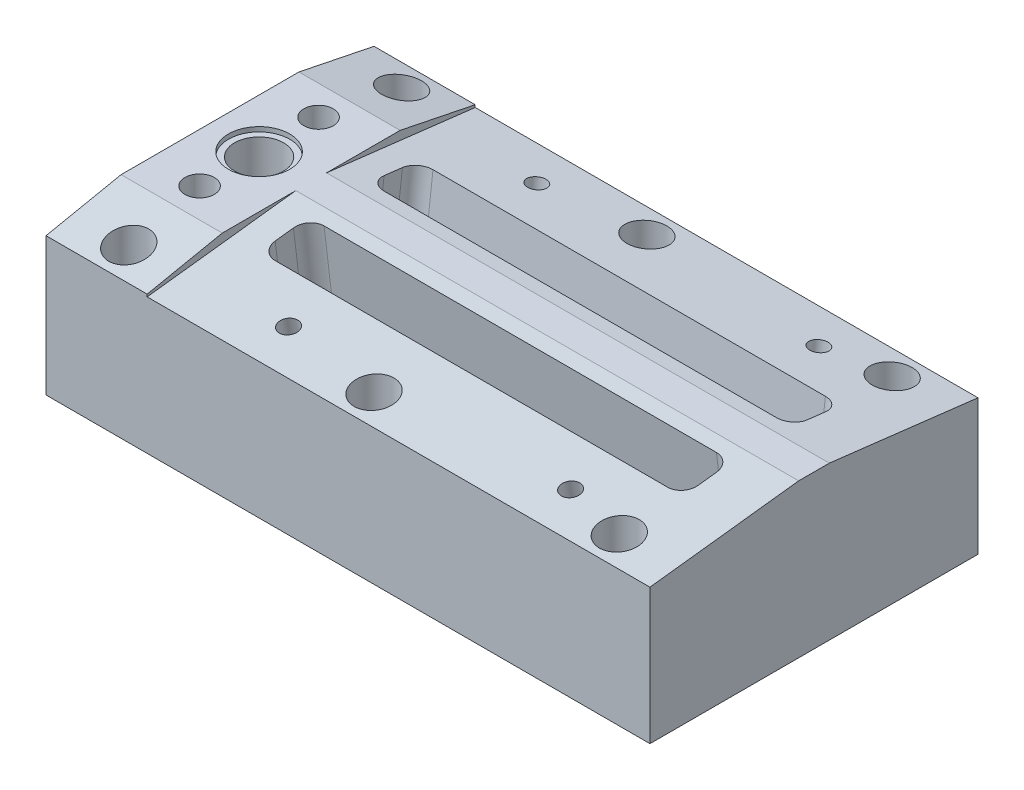
SolidWorks part; units mm, degrees
ref_plane "Front Plane" through (0, 0, 0) normal (0, 0, 1) x (1, 0, 0)
ref_plane "Top Plane" through (0, 0, 0) normal (0, 1, 0) x (1, 0, 0)
ref_plane "Right Plane" through (0, 0, 0) normal (1, 0, 0) x (0, 0, -1)
sketch "Sketch1" plane through (0, 0, 0) normal (0, 1, 0) x (1, 0, 0)
  line L1 (0, 0) -> (197, 0)
  line L2 (0, 0) -> (0, 107)
  line L3 (0, 107) -> (197, 107)
  line L4 (197, 0) -> (197, 107)
  dimension "D1" = 197
  dimension "D2" = 107
extrude "Boss-Extrude1" add sketch "Sketch1" along normal blind 50
ref_plane "Left" through (197, 0, 0) normal (1, 0, 0) x (0, 0, -1)
ref_plane "Bot" through (0, 50, 0) normal (0, 1, 0) x (1, 0, 0)
sketch "Sketch4" plane through (0, 0, 0) normal (0, 1, 0) x (1, 0, 0)
  line L0 (0, 107) -> (0, 0) construction
  line L1 (7.5, 31) -> (189.5, 31)
  line L2 (7.5, 31) -> (7.5, 76)
  line L3 (7.5, 76) -> (189.5, 76)
  line L4 (189.5, 31) -> (189.5, 76)
  line L5 (0, 0) -> (197, 0) construction
  dimension "D1" = 182
  dimension "D2" = 7.5
  dimension "D3" = 45
  dimension "D4" = 31
extrude "Cut-Extrude2" cut sketch "Sketch4" along normal blind 25
sketch "Sketch5" plane through (197, 0, 0) normal (1, 0, 0) x (0, 0, -1)
  line L0 (58.5, 50) -> (107, 44.2167)
  line L1 (0, 50) -> (107, 50) construction
  line L2 (107, 44.2167) -> (107, 50)
  line L3 (107, 50) -> (58.5, 50)
  line L4 (107, 50) -> (107, 0) construction
  point P4 (107, 50)
  point P6 (0, 0)
  point P7 (107, 50)
  dimension "D1" = 6.8
  dimension "D2" = 48.5
extrude "Cut-Extrude3" cut sketch "Sketch5" against normal blind 164
sketch "Sketch18" plane through (197, 0, 0) normal (1, 0, 0) x (0, 0, -1)
  line L0 (0, 44.2167) -> (0, 50)
  line L1 (0, 50) -> (0, 0) construction
  line L2 (0, 50) -> (48.5, 50)
  line L3 (48.5, 50) -> (0, 44.2167)
  line L4 (0, 50) -> (58.5, 50) construction
  dimension "D1" = 48.5
  dimension "D2" = 6.8
extrude "Cut-Extrude12" cut sketch "Sketch18" against normal up to surface (164 mm away) up to face at (33, 48.0722, -90.8333)
ref_plane "Plane3" through (0, 56.1769, -6.6987) normal (0, 0.993, -0.1184) x (1, 0, 0)
sketch "Sketch6" plane through (0, 56.1769, -6.6987) normal (0, 0.993, -0.1184) x (1, 0, 0)
  line L0 (197, 52.1683) -> (197, 101.0119) construction
  line L1 (47, 73.0456) -> (175, 73.0456)
  line L2 (42, 68.0456) -> (42, 62.0119)
  line L3 (47, 57.0119) -> (175, 57.0119)
  line L4 (180, 68.0456) -> (180, 62.0119)
  line L13 (33, 101.0119) -> (197, 101.0119) construction
  arc A0 (175, 73.0456) -> (180, 68.0456) centre (175, 68.0456) cw
  arc A1 (175, 57.0119) -> (180, 62.0119) centre (175, 62.0119) ccw
  arc A2 (42, 62.0119) -> (47, 57.0119) centre (47, 62.0119) ccw
  arc A3 (47, 73.0456) -> (42, 68.0456) centre (47, 68.0456) ccw
  point P12 (180, 65.0287)
  dimension "D1" = 5
  dimension "D2" = 138
  dimension "D3" = 6.0337
  dimension "D4" = 17
  dimension "D5" = 44
sketch "Sketch7" plane through (0, 0, 0) normal (1, 0, 0) x (0, 0, -1)
  line L1 (107, 50) -> (107, 0) construction
  line L2 (107, 50) -> (0, 50) construction
  line L3 (107, 50) -> (107, 45)
  line L5 (107, 45) -> (82.5051, 50)
  line L6 (107, 50) -> (82.5051, 50)
  line L7 (0, 45) -> (0, 50)
  line L8 (0, 50) -> (0, 0) construction
  line L9 (0, 50) -> (24.4949, 50)
  line L10 (24.4949, 50) -> (0, 45)
  dimension "D1" = 25
  dimension "D2" = 45
  dimension "D3" = 45
  dimension "D4" = 25
extrude "Cut-Extrude5" cut sketch "Sketch7" along normal through all
sketch "Sketch9" plane through (0, 50, 0) normal (0, 1, 0) x (1, 0, 0)
  line L0 (0, 82.5051) -> (0, 24.4949) construction
  circle A0 centre (16, 53.5) radius 8
  point P6 (0, 53.5)
  dimension "D1" = 16
  dimension "D2" = 16
extrude "Cut-Extrude6" cut sketch "Sketch9" against normal blind 171
sketch "Sketch10" plane through (0, 50, 0) normal (0, 1, 0) x (1, 0, 0)
  circle A0 centre (16, 53.5) radius 10
  dimension "D1" = 20
extrude "Cut-Extrude7" cut sketch "Sketch10" against normal blind 1.5
sketch "Sketch11" plane through (0, 50, 0) normal (0, 1, 0) x (1, 0, 0)
  line L0 (33, 82.5051) -> (0, 82.5051) construction
  line L1 (16, 61.5) -> (16, 53.5) construction
  line L2 (33, 24.4949) -> (0, 24.4949) construction
  circle A0 centre (16, 72.9051) radius 4.8
  circle A1 centre (16, 34.0949) radius 4.8
  circle A6 centre (16, 53.5) radius 8 construction
  dimension "D1" = 9.6
  dimension "D3" = 9.6
  dimension "D2" = 9.6
  dimension "D4" = 9.6
extrude "Cut-Extrude8" cut sketch "Sketch11" against normal blind 12.5
sketch "Sketch12" plane through (0, 50, 0) normal (0, 1, 0) x (1, 0, 0)
  line L0 (0, 82.5051) -> (0, 107) construction
  line L2 (33, 107) -> (0, 107) construction
  line L3 (33, 0) -> (0, 0) construction
  circle A0 centre (18, 98) radius 6.5
  circle A1 centre (98, 9) radius 6.5
  circle A2 centre (178, 9) radius 6.5
  circle A3 centre (18, 9) radius 6.5
  circle A4 centre (98, 98) radius 6.5
  circle A5 centre (178, 98) radius 6.5
  dimension "D1" = 13
  dimension "D2" = 13
  dimension "D3" = 13
  dimension "D4" = 13
  dimension "D5" = 13
  dimension "D6" = 13
  dimension "D7" = 80
  dimension "D8" = 18
  dimension "D9" = 80
  dimension "D10" = 9
  dimension "D11" = 9
extrude "Cut-Extrude9" cut sketch "Sketch12" against normal through all
sketch "Sketch13" plane through (0, 56.1769, -6.6987) normal (0, 0.993, -0.1184) x (1, 0, 0)
  line L0 (33, 52.1683) -> (33, 101.0119) construction
  line L1 (33, 101.0119) -> (197, 101.0119) construction
  line L2 (197, 52.1683) -> (197, 101.0119) construction
  circle A0 centre (66, 88.0119) radius 3
  circle A1 centre (158, 88.0119) radius 3
  dimension "D1" = 6
  dimension "D4" = 6
  dimension "D2" = 33
  dimension "D3" = 13
  dimension "D5" = 39
extrude "Cut-Extrude10" cut sketch "Sketch13" against normal blind 26.5
ref_plane "Plane8" through (0, 43.2, 8.8182) normal (0, 0.9798, 0.2) x (1, 0, 0)
sketch "Sketch14" plane through (0, 43.2, 8.8182) normal (0, 0.9798, 0.2) x (1, 0, 0)
  line L0 (33, 9) -> (0, 9) construction
  line L1 (33, 67.3181) -> (33, 113.6815) construction
  line L2 (197, 9) -> (197, 34) construction
  circle A0 centre (66, 22) radius 3
  circle A1 centre (158, 22) radius 3
  dimension "D1" = 6
  dimension "D2" = 6
  dimension "D3" = 13
  dimension "D4" = 33
  dimension "D5" = 39
extrude "Cut-Extrude11" cut sketch "Sketch14" against normal blind 26.5
ref_plane "Plane9" through (0, 43.5968, 5.1986) normal (0, 0.993, 0.1184) x (1, 0, 0)
sketch "Sketch23" plane through (0, 43.5968, 5.1986) normal (0, 0.993, 0.1184) x (1, 0, 0)
  line L0 (33, 5.2354) -> (197, 5.2354) construction
  line L1 (47, 49.2354) -> (175, 49.2354)
  line L2 (42, 44.2354) -> (42, 38.2354)
  line L3 (47, 33.2354) -> (175, 33.2354)
  line L4 (180, 44.2354) -> (180, 38.2354)
  line L5 (197, 5.2354) -> (197, 54.079) construction
  arc A0 (175, 49.2354) -> (180, 44.2354) centre (175, 44.2354) cw
  arc A1 (175, 33.2354) -> (180, 38.2354) centre (175, 38.2354) ccw
  arc A2 (42, 38.2354) -> (47, 33.2354) centre (47, 38.2354) ccw
  arc A3 (47, 49.2354) -> (42, 44.2354) centre (47, 44.2354) ccw
  point P10 (180, 49.2354)
  point P15 (42, 33.2354)
  point P18 (42, 49.2354)
  dimension "D5" = 5
  dimension "D1" = 138
  dimension "D2" = 16
  dimension "D3" = 44
  dimension "D4" = 17
extrude "Cut-Extrude14" cut sketch "Sketch23" against normal blind 35
extrude "Cut-Extrude15" cut sketch "Sketch6" against normal blind 130
